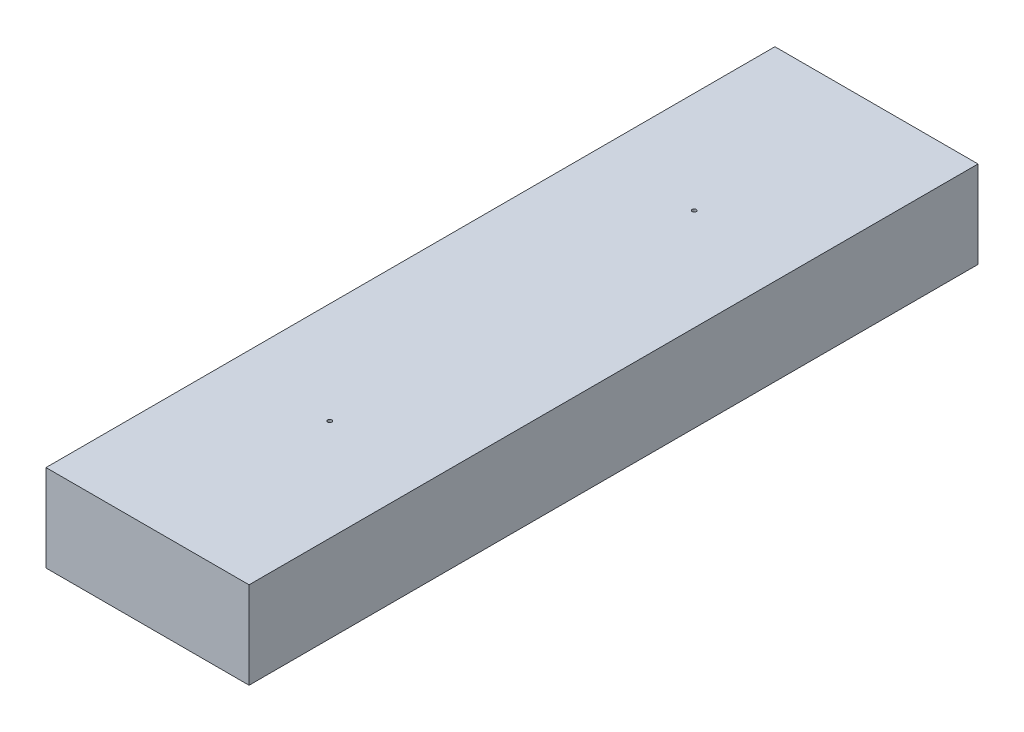
SolidWorks part; units mm, degrees
material "Pine"
ref_plane "Front Plane" through (0, 0, 0) normal (0, 0, 1) x (1, 0, 0)
ref_plane "Top Plane" through (0, 0, 0) normal (0, 1, 0) x (1, 0, 0)
ref_plane "Right Plane" through (0, 0, 0) normal (1, 0, 0) x (0, 0, -1)
sketch "Sketch1" plane through (0, 0, 0) normal (0, 0, 1) x (1, 0, 0)
  line L1 (0, 0) -> (88.9, 0)
  line L2 (0, 0) -> (0, 38.1)
  line L3 (0, 38.1) -> (88.9, 38.1)
  line L4 (88.9, 0) -> (88.9, 38.1)
  dimension "D1" = 88.9
  dimension "D2" = 38.1
extrude "Boss-Extrude1" add sketch "Sketch1" along normal blind 319.0875
sketch "Sketch2" plane through (0, 0, 0) normal (0, -1, 0) x (1, 0, 0)
  line L0 (44.45, 0) -> (44.45, 159.5437) construction
  line L1 (44.45, 159.5437) -> (44.45, 319.0875) construction
  line L2 (0, 319.0875) -> (88.9, 319.0875) construction
  line L3 (0, 0) -> (88.9, 0) construction
  circle A0 centre (44.45, 79.7719) radius 0.889
  circle A1 centre (44.45, 239.3156) radius 0.889
  dimension "D1" = 1.778
extrude "Cut-Extrude1" cut sketch "Sketch2" against normal up to surface (38.1 mm away) up to face at (44.45, 38.1, 159.5437)
equation "\"length\"= 13 - ( 7 / 16 )"
equation "\"D1@Boss-Extrude1\"=\"length\""
